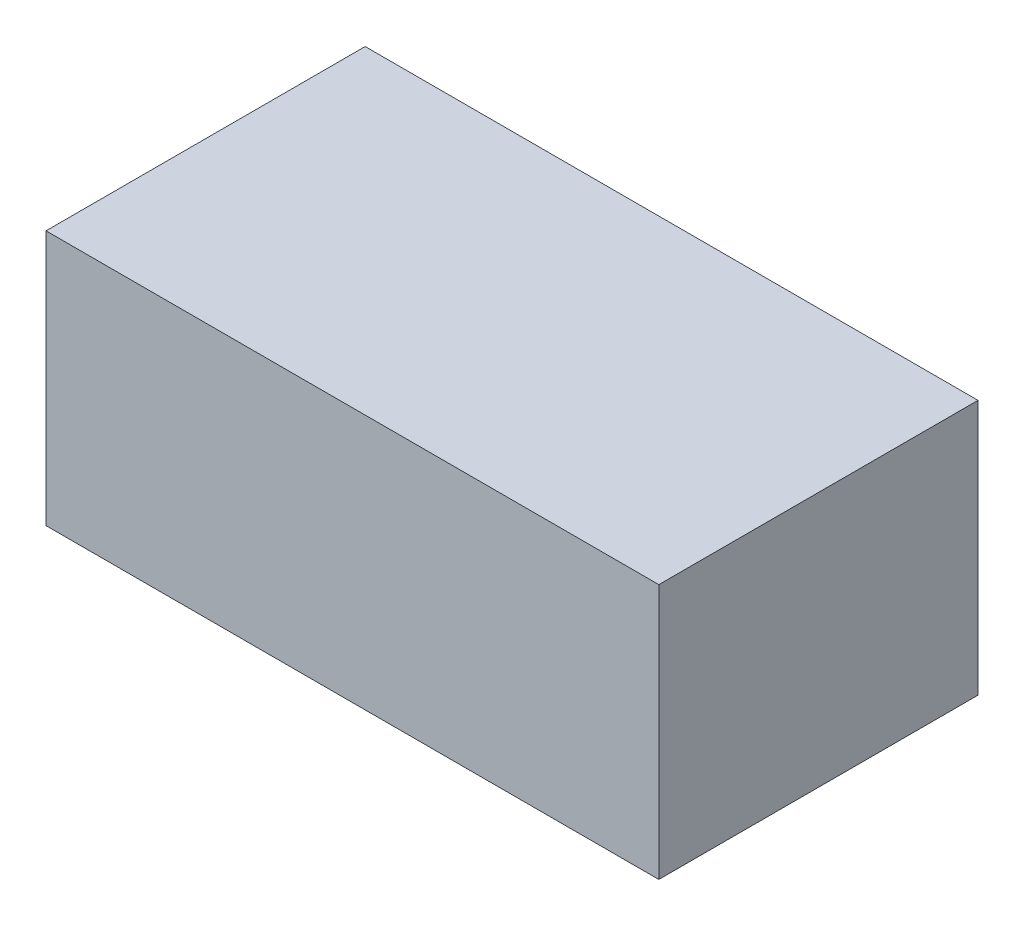
SolidWorks part; units mm, degrees
ref_plane "前视基准面" through (0, 0, 0) normal (0, 0, 1) x (1, 0, 0)
ref_plane "上视基准面" through (0, 0, 0) normal (0, 1, 0) x (1, 0, 0)
ref_plane "右视基准面" through (0, 0, 0) normal (1, 0, 0) x (0, 0, -1)
other "Configuration Table"
sketch "草图2" plane through (0, 0, 0) normal (0, 1, 0) x (1, 0, 0)
  line L1 (-24, 12.5) -> (24, 12.5)
  line L2 (-24, 12.5) -> (-24, -12.5)
  line L3 (-24, -12.5) -> (24, -12.5)
  line L4 (24, 12.5) -> (24, -12.5)
  line L5 (-24, 12.5) -> (24, -12.5) construction
  line L6 (-24, -12.5) -> (24, 12.5) construction
  point P0 (0, 0)
  dimension "D1" = 48
  dimension "D2" = 25
extrude "凸台-拉伸1" add sketch "草图2" along normal blind 20
